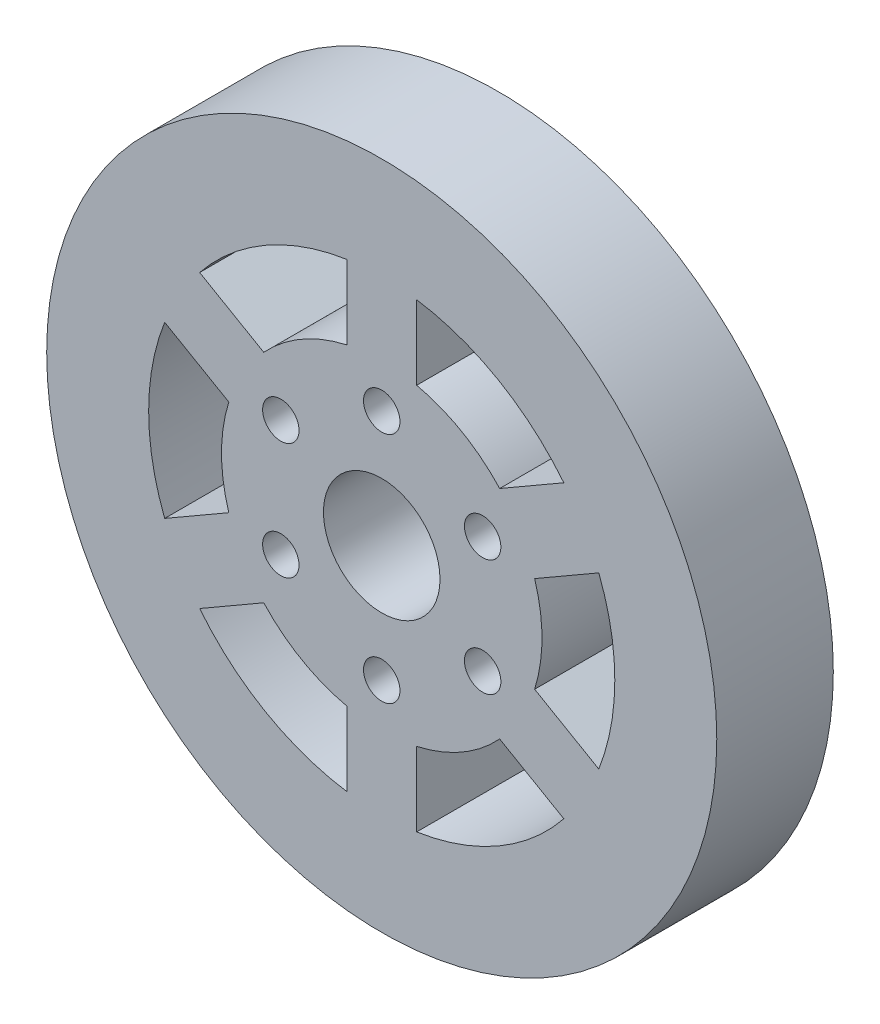
SolidWorks part; units mm, degrees
ref_plane "Front Plane" through (0, 0, 0) normal (0, 0, 1) x (1, 0, 0)
ref_plane "Top Plane" through (0, 0, 0) normal (0, 1, 0) x (1, 0, 0)
ref_plane "Right Plane" through (0, 0, 0) normal (1, 0, 0) x (0, 0, -1)
sketch "Sketch2" plane through (0, 0, 0) normal (0, 0, 1) x (1, 0, 0)
  circle A0 centre (0, 0) radius 73.025
  dimension "D1" = 146.05
sketch "Sketch3" plane through (0, 0, 0) normal (0, 0, 1) x (1, 0, 0)
  circle A0 centre (0, 0) radius 73.025
  dimension "D1" = 146.05
extrude "Boss-Extrude2" add sketch "Sketch3" against normal blind 25.4
sketch "Sketch4" plane through (0, 0, 0) normal (0, 0, 1) x (1, 0, 0)
  line L0 (0, -50.8) -> (0, -29.3688)
  line L1 (-43.9941, 25.4) -> (-25.4341, 14.6844)
  line L2 (43.9941, 25.4) -> (25.4341, 14.6844)
  line L3 (7.62, -50.8) -> (7.62, -4.3994)
  line L4 (40.1841, 31.9991) -> (4.9888, 11.6791)
  line L5 (-47.8041, 18.8009) -> (-12.6088, -1.5191)
  line L6 (-7.62, -50.8) -> (-7.62, -10.16)
  line L7 (47.8041, 18.8009) -> (12.6088, -1.5191)
  line L8 (-40.1841, 31.9991) -> (-4.9888, 11.6791)
  line L9 (-25.4341, -14.6844) -> (-43.9941, -25.4)
  line L10 (43.9941, 25.4) -> (-43.9941, -25.4) construction
  line L11 (-18.56, 10.7156) -> (-10.9985, 6.35)
  line L12 (-43.9941, 25.4) -> (43.9941, -25.4) construction
  line L13 (0, 29.3688) -> (0, 50.8)
  line L14 (0, -50.8) -> (0, 50.8) construction
  line L15 (18.56, 10.7156) -> (10.9985, 6.35)
  line L16 (25.4341, -14.6844) -> (43.9941, -25.4)
  line L17 (0, -21.4313) -> (0, -12.7)
  line L19 (-7.62, -50.8) -> (-7.62, 50.8) construction
  line L20 (-10.9985, -6.35) -> (-18.56, -10.7156)
  line L21 (4.9888, -11.6791) -> (40.1841, -31.9991)
  line L22 (-47.8041, 18.8009) -> (40.1841, -31.9991) construction
  line L23 (-12.6088, 1.5191) -> (-47.8041, -18.8009)
  line L24 (40.1841, 31.9991) -> (-47.8041, -18.8009) construction
  line L26 (-7.62, 10.16) -> (-7.62, 50.8)
  line L27 (0, 12.7) -> (0, 21.4313)
  line L28 (12.6088, 1.5191) -> (47.8041, -18.8009)
  line L29 (-40.1841, 31.9991) -> (47.8041, -18.8009) construction
  line L31 (10.9985, -6.35) -> (18.56, -10.7156)
  line L32 (-4.9888, -11.6791) -> (-40.1841, -31.9991)
  line L33 (47.8041, 18.8009) -> (-40.1841, -31.9991) construction
  line L34 (7.62, 10.16) -> (7.62, 50.8)
  line L35 (7.62, -50.8) -> (7.62, 50.8) construction
  circle A0 centre (0, 0) radius 50.8
  arc A1 (-19.7502, -15.9715) -> (-3.9566, -25.0899) centre (0, 0) ccw
  circle A2 centre (0, 25.4) radius 3.9687
  circle A3 centre (21.997, 12.7) radius 3.9688
  circle A4 centre (21.997, -12.7) radius 3.9688
  circle A5 centre (0, -25.4) radius 3.9688
  circle A6 centre (-21.997, -12.7) radius 3.9688
  circle A7 centre (-21.997, 12.7) radius 3.9688
  circle A8 centre (0, 0) radius 12.7
  circle A9 centre (0, 0) radius 34.925
  arc A10 (-23.7068, 9.1184) -> (-23.7068, -9.1184) centre (0, 0) ccw
  arc A11 (-3.9566, 25.0899) -> (-19.7502, 15.9715) centre (0, 0) ccw
  arc A12 (19.7502, 15.9715) -> (3.9566, 25.0899) centre (0, 0) ccw
  arc A13 (23.7068, -9.1184) -> (23.7068, 9.1184) centre (0, 0) ccw
  arc A14 (3.9566, -25.0899) -> (19.7502, -15.9715) centre (0, 0) ccw
  point P16 (0, 0)
  point P36 (0, 0)
  dimension "D3" = 101.6
  dimension "D4" = 69.85
  dimension "D5" = 7.9375
  dimension "D8" = 25.4
  dimension "D1" = 60
  dimension "D2" = 60
  dimension "D6" = 7.62
  dimension "D7" = 7.62
extrude "Cut-Extrude1" cut sketch "Sketch4" against normal through all both and the other way through all
